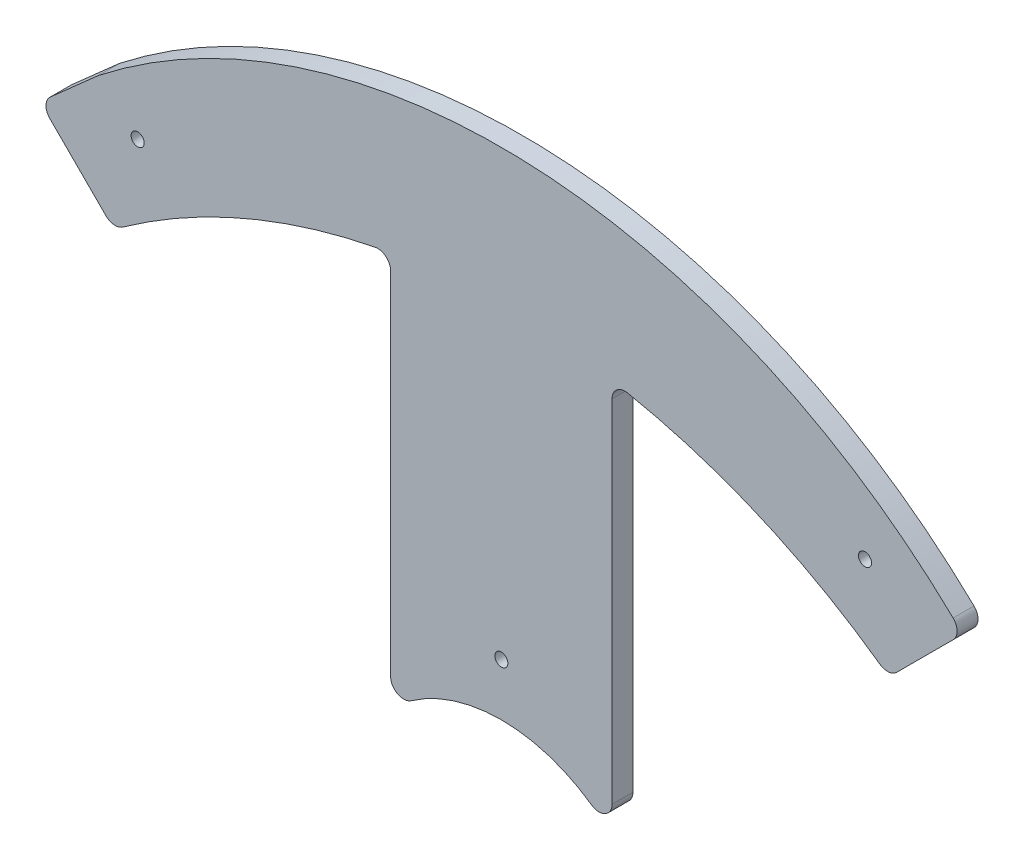
SolidWorks part; units mm, degrees
ref_plane "Front Plane" through (0, 0, 0) normal (0, 0, 1) x (1, 0, 0)
ref_plane "Top Plane" through (0, 0, 0) normal (0, 1, 0) x (1, 0, 0)
ref_plane "Right Plane" through (0, 0, 0) normal (1, 0, 0) x (0, 0, -1)
sketch "Sketch1" plane through (0, 0, 0) normal (0, 0, 1) x (1, 0, 0)
  line L6 (-111.0285, -74.12) -> (-96.8891, -88.2594)
  line L7 (65.7482, -74.12) -> (51.6088, -88.2594)
  line L9 (-1.4269, -141.2951) -> (-1.4269, -65.6315)
  line L10 (-43.8533, -141.2951) -> (-43.8533, -65.6315)
  line L12 (-111.0285, -74.12) -> (-99.8046, -64.1689) construction
  line L13 (-111.0285, -74.12) -> (-101.0285, -84.12)
  line L14 (-101.0285, -84.12) -> (-111.0285, -74.12)
  line L16 (-111.0285, -74.12) -> (-100.421, -63.5125)
  line L17 (-99.7822, -64.1513) -> (-100.421, -63.5125)
  line L18 (-22.6401, -132.5083) -> (-22.6401, -122.5083)
  line L19 (-22.6401, -121.2583) -> (-22.6401, -132.5083)
  arc A2 (-22.6401, -37.5083) -> (-111.0285, -74.12) centre (-22.6401, -162.5083) ccw
  arc A3 (-22.6401, -37.5083) -> (65.7482, -74.12) centre (-22.6401, -162.5083) cw
  arc A4 (51.6088, -88.2594) -> (-1.4269, -65.6315) centre (-22.6401, -188.8183) ccw
  arc A5 (-1.4269, -141.2951) -> (-43.8533, -141.2951) centre (-22.6401, -162.5083) ccw
  circle A6 centre (-92.3185, -71.021) radius 1.25
  circle A7 centre (47.0383, -71.021) radius 1.25
  circle A8 centre (-22.6401, -122.5083) radius 1.25
  arc A9 (-43.8533, -65.6315) -> (-96.8891, -88.2594) centre (-22.6401, -188.8183) ccw
  point P2 (-43.8533, -65.6315)
  point P6 (-22.6401, -100.0083)
  point P11 (-1.4269, -65.6315)
  point P13 (-22.6401, -132.5083)
  point P20 (-92.3185, -71.021)
  dimension "D1" = 26.31
  dimension "D2" = 125
  dimension "D3" = 250
  dimension "D4" = 60
  dimension "D5" = 15
  dimension "D7" = 2.5
  dimension "D10" = 2.5
  dimension "D6" = 10
  dimension "D8" = 10
  dimension "D9" = 10
extrude "Boss-Extrude1" add sketch "Sketch1" along normal blind 4
fillet "Fillet1" radius 2.5 2 edges at (65.7482, -74.12, 2) (51.6088, -88.2594, 2)
fillet "Fillet2" radius 2.5 2 edges at (-43.8533, -141.2951, 2) (-1.4269, -141.2951, 2)
fillet "Fillet3" radius 2.5 2 edges at (-111.0285, -74.12, 2) (-96.8891, -88.2594, 2)
fillet "Fillet4" radius 2.5 1 edges at (-43.8533, -65.6315, 2)
fillet "Fillet5" radius 2.5 1 edges at (-1.4269, -65.6315, 2)
